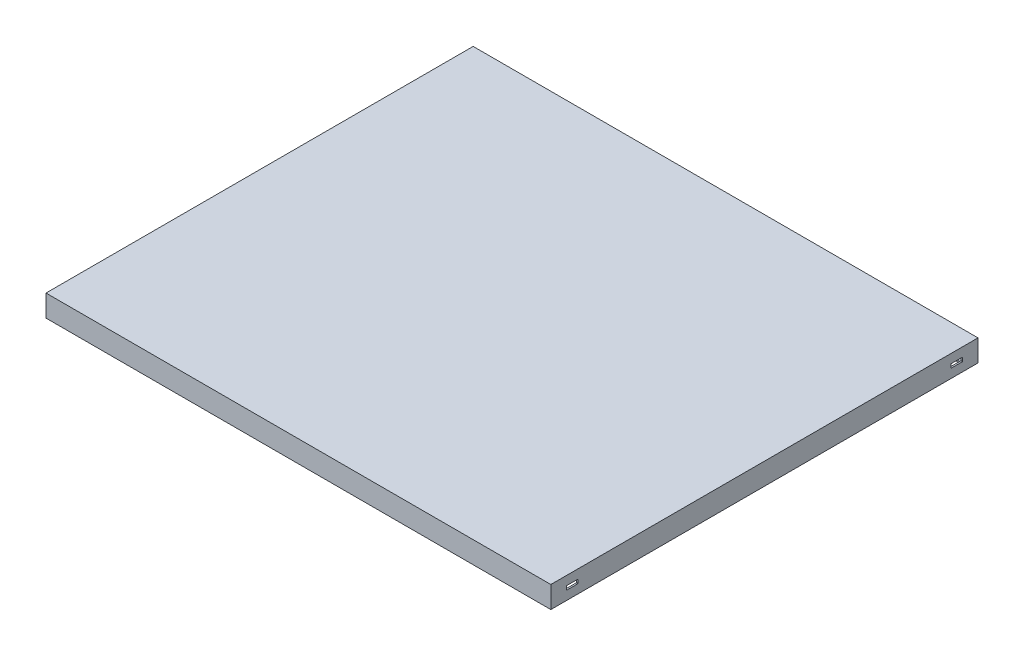
SolidWorks part; units mm, degrees
ref_plane "Alzado" through (0, 0, 0) normal (0, 0, 1) x (1, 0, 0)
ref_plane "Planta" through (0, 0, 0) normal (0, 1, 0) x (1, 0, 0)
ref_plane "Vista lateral" through (0, 0, 0) normal (1, 0, 0) x (0, 0, -1)
sketch "Croquis1" plane through (0, 0, 0) normal (0, 1, 0) x (1, 0, 0)
  line L1 (-325, -275) -> (325, -275)
  line L2 (-325, -275) -> (-325, 275)
  line L3 (-325, 275) -> (325, 275)
  line L4 (325, -275) -> (325, 275)
  line L5 (-325, -275) -> (325, 275) construction
  line L6 (-325, 275) -> (325, -275) construction
  point P0 (0, 0)
  dimension "D1" = 550
  dimension "D2" = 650
extrude "Saliente-Extruir1" add sketch "Croquis1" along normal blind 28
shell "Vaciado1" thickness 2
sketch "Croquis2" plane through (0, 0, 273) normal (0, 0, -1) x (-1, 0, 0)
  line L0 (-323, 26) -> (-323, 0) construction
  line L1 (323, 0) -> (-323, 0)
  line L2 (323, 0) -> (323, 2)
  line L3 (323, 2) -> (-323, 2)
  line L4 (-323, 0) -> (-323, 2)
  dimension "D1" = 2
extrude "Saliente-Extruir2" add sketch "Croquis2" along normal blind 10
sketch "Croquis3" plane through (0, 0, -273) normal (0, 0, 1) x (1, 0, 0)
  line L0 (323, 26) -> (323, 0) construction
  line L1 (-323, 0) -> (323, 0)
  line L2 (-323, 0) -> (-323, 2)
  line L3 (-323, 2) -> (323, 2)
  line L4 (323, 0) -> (323, 2)
  dimension "D1" = 2
extrude "Saliente-Extruir3" add sketch "Croquis3" along normal blind 10
sketch "Croquis4" plane through (-325, 0, 0) normal (-1, 0, 0) x (0, 0, 1)
  line L3 (-255, 11.5) -> (-240, 11.5)
  line L4 (-255, 11.5) -> (-255, 16.5)
  line L5 (-255, 16.5) -> (-240, 16.5)
  line L6 (-240, 11.5) -> (-240, 16.5)
  line L7 (255, 11.5) -> (255, 16.5)
  line L8 (240, 11.5) -> (255, 11.5)
  line L9 (240, 16.5) -> (255, 16.5)
  line L10 (240, 11.5) -> (240, 16.5)
  dimension "D2" = 15
  dimension "D3" = 5
  dimension "D4" = 15
  dimension "D5" = 5
extrude "Cortar-Extruir1" cut sketch "Croquis4" against normal up to surface (650 mm away) up to face at (325, 14, 0)
